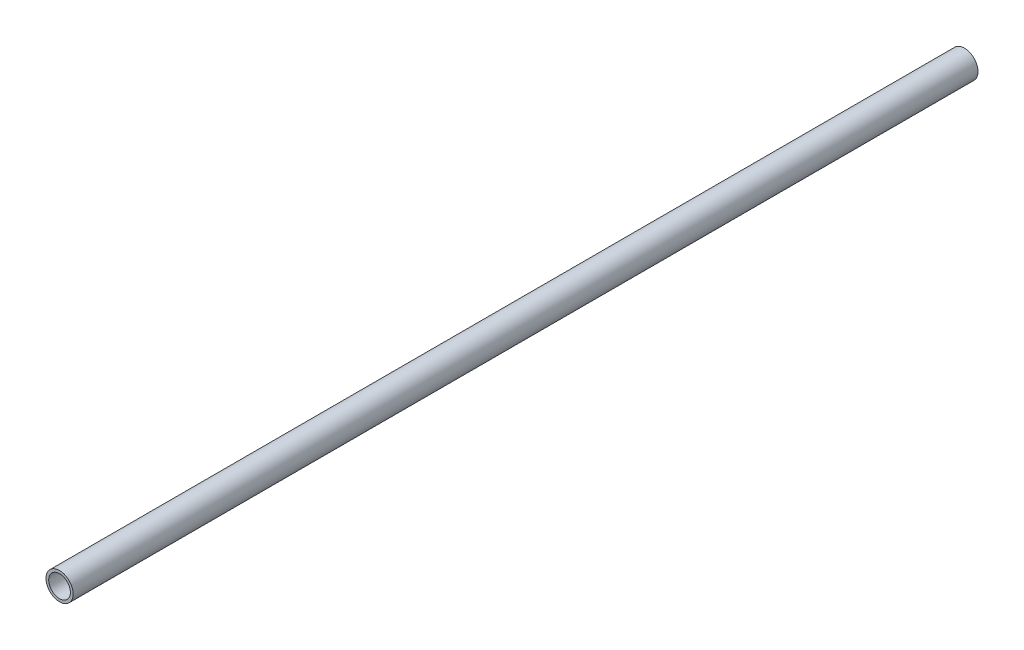
SolidWorks part; units mm, degrees
ref_plane "Front Plane" through (0, 0, 0) normal (0, 0, 1) x (1, 0, 0)
ref_plane "Top Plane" through (0, 0, 0) normal (0, 1, 0) x (1, 0, 0)
ref_plane "Right Plane" through (0, 0, 0) normal (1, 0, 0) x (0, 0, -1)
sketch "Sketch1" plane through (0, 0, 0) normal (0, 0, 1) x (1, 0, 0)
  circle A0 centre (0, 0) radius 15
  dimension "D1" = 30
extrude "Boss-Extrude1" add sketch "Sketch1" along normal blind 1000
sketch "Sketch2" plane through (0, 0, 0) normal (0, 0, 1) x (1, 0, 0)
  circle A0 centre (0, 0) radius 12
  dimension "D1" = 24
extrude "Cut-Extrude1" cut sketch "Sketch2" along normal blind 1000
